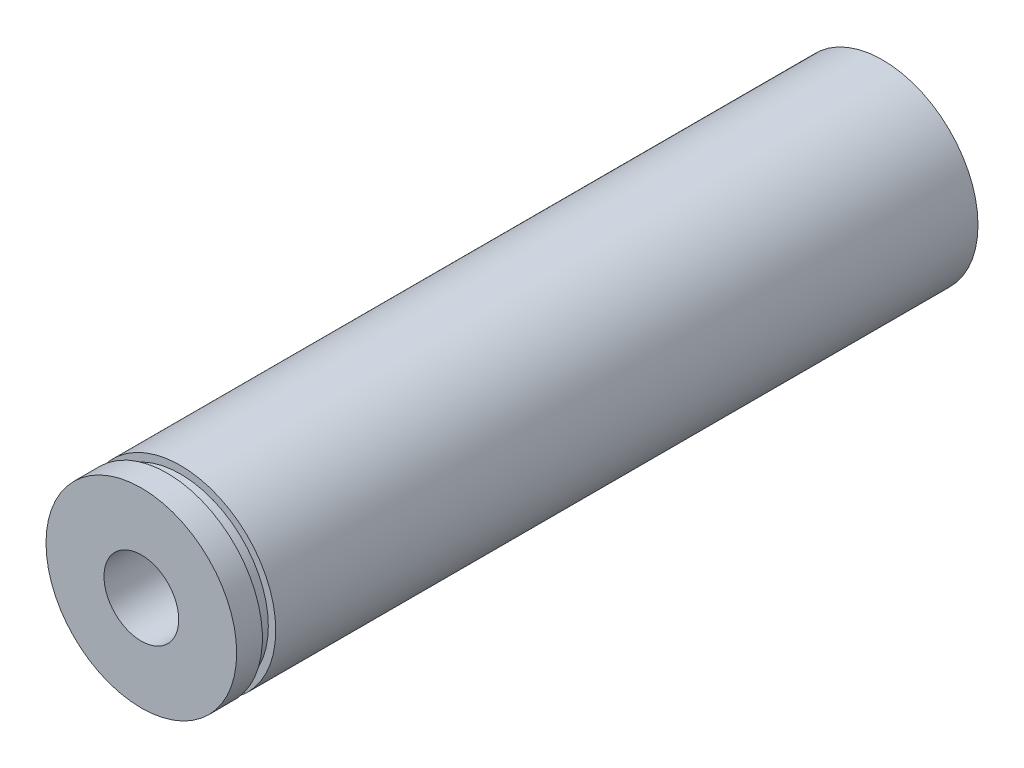
SolidWorks part; units mm, degrees
ref_plane "Front Plane" through (0, 0, 0) normal (0, 0, 1) x (1, 0, 0)
ref_plane "Top Plane" through (0, 0, 0) normal (0, 1, 0) x (1, 0, 0)
ref_plane "Right Plane" through (0, 0, 0) normal (1, 0, 0) x (0, 0, -1)
sketch "Sketch1" plane through (0, 0, 0) normal (0, 0, 1) x (1, 0, 0)
  circle A0 centre (0, 0) radius 6.35
  circle A1 centre (0, 0) radius 2.4892
  dimension "D1" = 12.7
  dimension "D2" = 4.9784
extrude "Boss-Extrude1" add sketch "Sketch1" along normal mid plane 49.3776
sketch "Sketch2" plane through (0, 0, 0) normal (1, 0, 0) x (0, 0, -1)
  line L0 (-2.4056, 0) -> (1.6345, 0) construction
  line L1 (-22.9743, 6.858) -> (-22.0853, 6.858)
  line L2 (-22.9743, 6.858) -> (-22.9743, 5.8547)
  line L3 (-22.9743, 5.8547) -> (-22.0853, 5.8547)
  line L4 (-22.0853, 6.858) -> (-22.0853, 5.8547)
  line L5 (-24.6888, 6.35) -> (-24.6888, -6.35) construction
  point P7 (-23.0229, 5.8547)
  dimension "D1" = 0.889
  dimension "D2" = 5.8547
  dimension "D3" = 1.7145
revolve "Cut-Revolve1" cut sketch "Sketch2" angle 360 about L0
